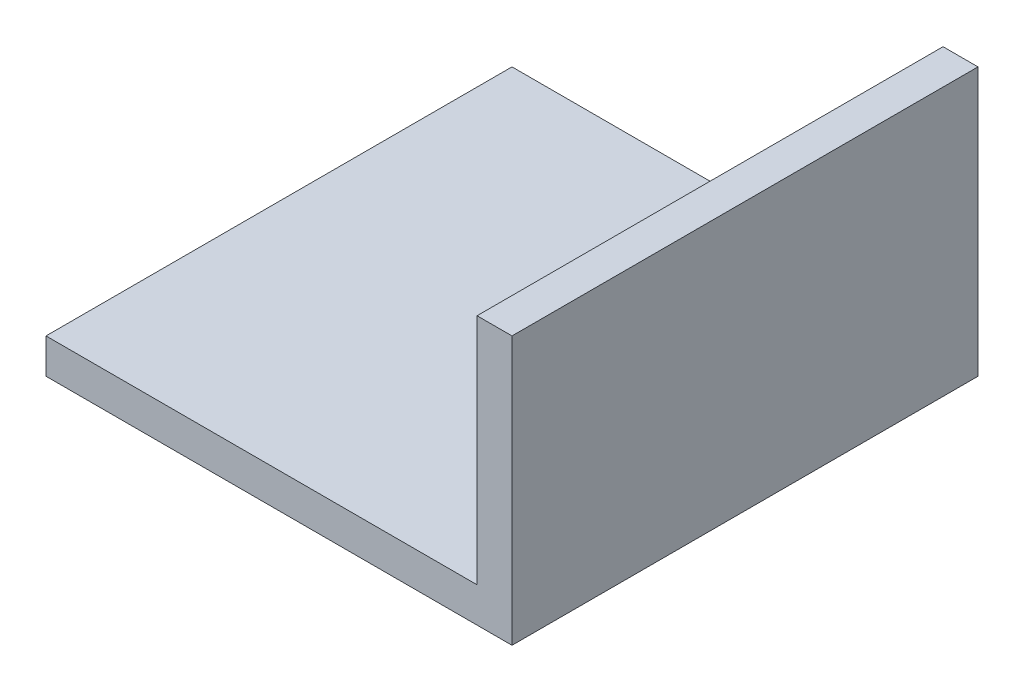
SolidWorks part; units mm, degrees
ref_plane "前视" through (0, 0, 0) normal (0, 0, 1) x (1, 0, 0)
ref_plane "上视" through (0, 0, 0) normal (0, 1, 0) x (1, 0, 0)
ref_plane "右视" through (0, 0, 0) normal (1, 0, 0) x (0, 0, -1)
sketch "Sketch1" plane through (0, 0, 0) normal (0, 1, 0) x (1, 0, 0)
  line L1 (0, 0) -> (40, 0)
  line L2 (0, 0) -> (0, 40)
  line L3 (0, 40) -> (40, 40)
  line L4 (40, 0) -> (40, 40)
  dimension "D1" = 40
  dimension "D2" = 40
extrude "Extrude1" add sketch "Sketch1" along normal blind 3
sketch "Sketch2" plane through (0, 3, 0) normal (0, 1, 0) x (1, 0, 0)
  line L0 (40, 40) -> (0, 40) construction
  line L1 (40, 0) -> (37, 0)
  line L2 (40, 0) -> (40, 40)
  line L3 (40, 40) -> (37, 40)
  line L4 (37, 0) -> (37, 40)
  dimension "D1" = 3
extrude "Extrude2" add sketch "Sketch2" along normal blind 20
